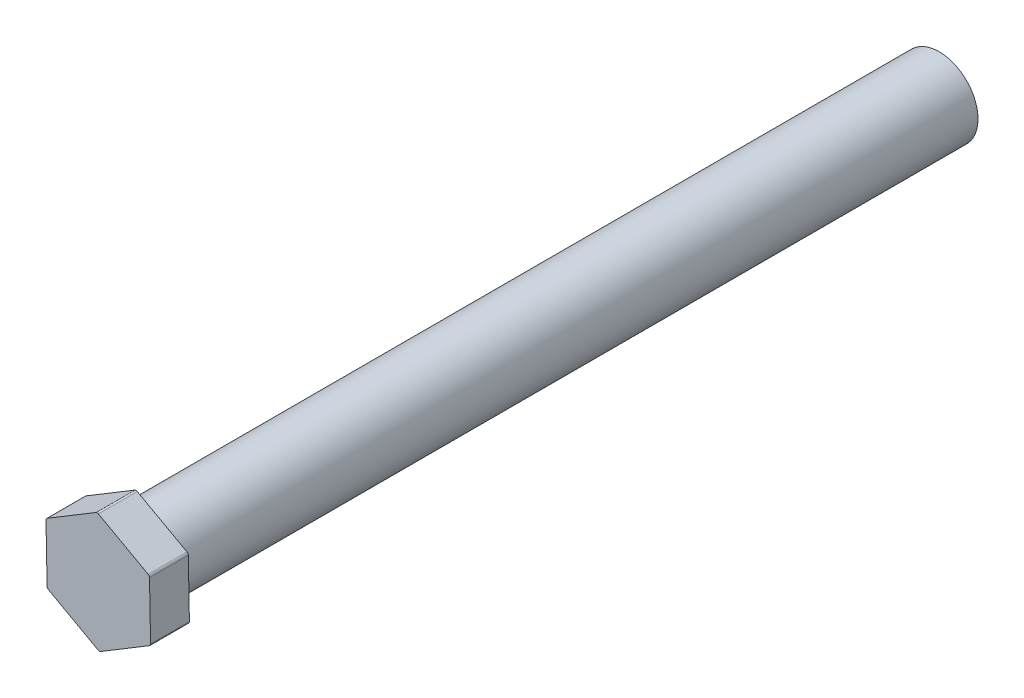
SolidWorks part; units mm, degrees
ref_plane "Front Plane" through (0, 0, 0) normal (0, 0, 1) x (1, 0, 0)
ref_plane "Top Plane" through (0, 0, 0) normal (0, 1, 0) x (1, 0, 0)
ref_plane "Right Plane" through (0, 0, 0) normal (1, 0, 0) x (0, 0, -1)
sketch "Sketch1" plane through (0, 0, 0) normal (0, 0, 1) x (1, 0, 0)
  circle A0 centre (-43.2, 0) radius 3
  circle A1 centre (-43.2, 0) radius 3 construction
extrude "Boss-Extrude1" add sketch "Sketch1" against normal blind 62 contours A0
sketch "Sketch2" plane through (0, 0, 0) normal (0, 0, 1) x (1, 0, 0)
  line L1 (-47.0544, -2.4423) -> (-43.2121, -4.563)
  line L2 (-43.0121, -4.5592) -> (-39.2544, -2.292)
  line L3 (-39.1577, -2.1169) -> (-39.2423, 2.271)
  line L4 (-39.3456, 2.4423) -> (-43.1879, 4.563)
  line L5 (-43.3879, 4.5592) -> (-47.1456, 2.292)
  line L6 (-47.2423, 2.1169) -> (-47.1577, -2.271)
  circle A0 centre (-43.2, 0) radius 3
  circle A1 centre (-43.2, 0) radius 3 construction
  circle A2 centre (-43.2, 0) radius 4.0007 construction
  arc A3 (-47.1456, 2.292) -> (-47.2423, 2.1169) centre (-47.0423, 2.1207) ccw
  arc A4 (-43.1879, 4.563) -> (-43.3879, 4.5592) centre (-43.2846, 4.3879) ccw
  arc A5 (-39.2423, 2.271) -> (-39.3456, 2.4423) centre (-39.4422, 2.2672) ccw
  arc A6 (-39.2544, -2.292) -> (-39.1577, -2.1169) centre (-39.3577, -2.1207) ccw
  arc A7 (-43.2121, -4.563) -> (-43.0121, -4.5592) centre (-43.1154, -4.3879) ccw
  arc A8 (-47.0544, -2.4423) -> (-47.1577, -2.271) centre (-46.9578, -2.2672) cw
  point P5 (-47.2, -0.0771)
  point P13 (-39.2, 0.0771)
  dimension "D2" = 0.2
  dimension "D1" = 8
extrude "Boss-Extrude2" add sketch "Sketch2" along normal blind 3 contours L5 A3 L6 A8 L1 A7 L2 A6 L3 A5 L4 A4
